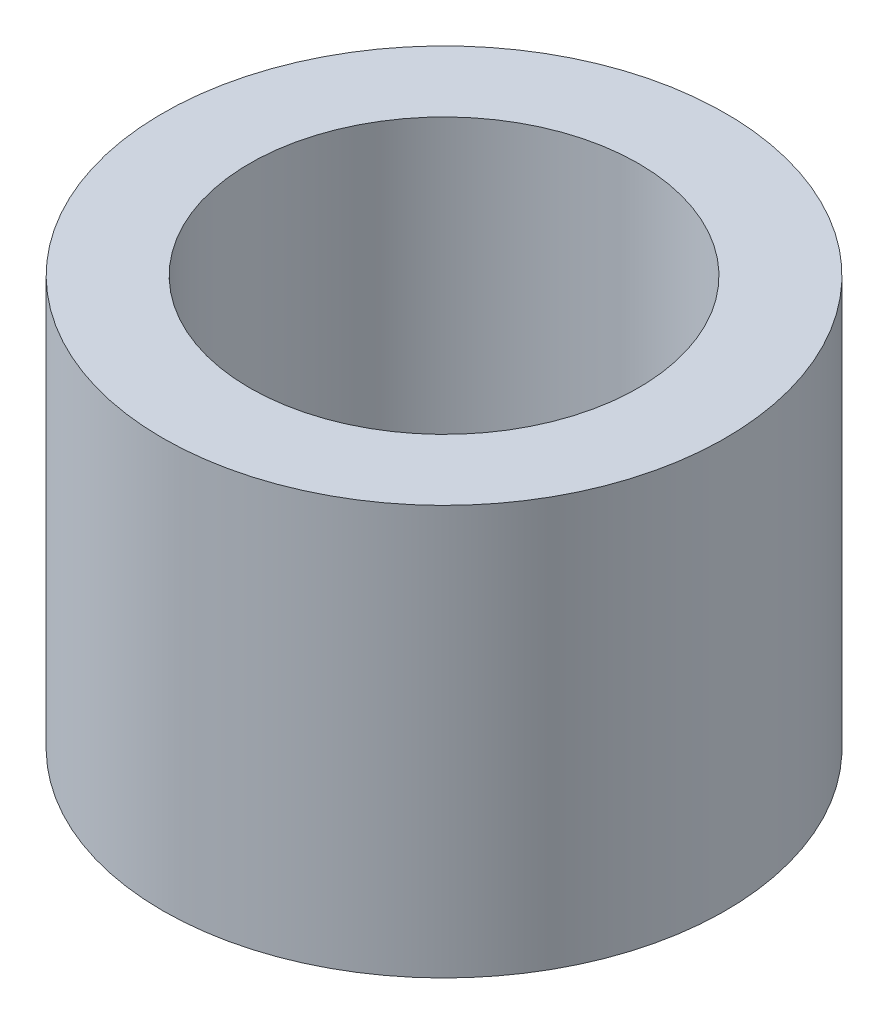
SolidWorks part; units mm, degrees
ref_plane "Front Plane" through (0, 0, 0) normal (0, 0, 1) x (1, 0, 0)
ref_plane "Top Plane" through (0, 0, 0) normal (0, 1, 0) x (1, 0, 0)
ref_plane "Right Plane" through (0, 0, 0) normal (1, 0, 0) x (0, 0, -1)
sketch "Sketch1" plane through (0, 0, 0) normal (0, 1, 0) x (1, 0, 0)
  circle A0 centre (0, 0) radius 1.9
  circle A1 centre (0, 0) radius 2.75
  dimension "D1" = 3.8
  dimension "D2" = 5.5
extrude "Boss-Extrude1" add sketch "Sketch1" along normal blind 4
